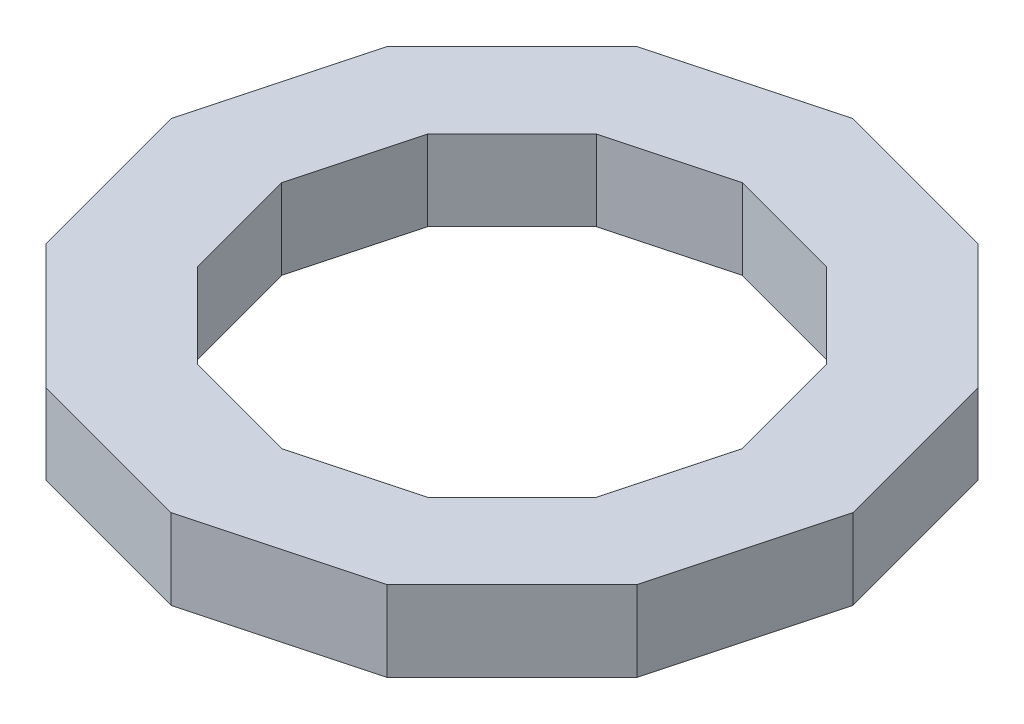
SolidWorks part; units mm, degrees
ref_plane "Front Plane" through (0, 0, 0) normal (0, 0, 1) x (1, 0, 0)
ref_plane "Top Plane" through (0, 0, 0) normal (0, 1, 0) x (1, 0, 0)
ref_plane "Right Plane" through (0, 0, 0) normal (1, 0, 0) x (0, 0, -1)
sketch "Sketch1" plane through (0, 0, 0) normal (0, 1, 0) x (1, 0, 0)
  line L0 (0, 0) -> (54.6679, 0) construction
  line L1 (54.6679, 0) -> (47.3438, 27.3339)
  line L2 (47.3438, 27.3339) -> (27.3339, 47.3438)
  line L3 (27.3339, 47.3438) -> (0, 54.6679)
  line L4 (0, 54.6679) -> (-27.3339, 47.3438)
  line L5 (-27.3339, 47.3438) -> (-47.3438, 27.3339)
  line L6 (-47.3438, 27.3339) -> (-54.6679, 0)
  line L7 (-54.6679, 0) -> (-47.3438, -27.3339)
  line L8 (-47.3438, -27.3339) -> (-27.3339, -47.3438)
  line L9 (-27.3339, -47.3438) -> (0, -54.6679)
  line L10 (0, -54.6679) -> (27.3339, -47.3438)
  line L11 (27.3339, -47.3438) -> (47.3438, -27.3339)
  line L12 (47.3438, -27.3339) -> (54.6679, 0)
  line L13 (80.9639, 0) -> (70.1168, 40.482)
  line L14 (70.1168, 40.482) -> (40.482, 70.1168)
  line L15 (40.482, 70.1168) -> (0, 80.9639)
  line L16 (0, 80.9639) -> (-40.482, 70.1168)
  line L17 (-40.482, 70.1168) -> (-70.1168, 40.482)
  line L18 (-70.1168, 40.482) -> (-80.9639, 0)
  line L19 (-80.9639, 0) -> (-70.1168, -40.482)
  line L20 (-70.1168, -40.482) -> (-40.482, -70.1168)
  line L21 (-40.482, -70.1168) -> (0, -80.9639)
  line L22 (0, -80.9639) -> (40.482, -70.1168)
  line L23 (40.482, -70.1168) -> (70.1168, -40.482)
  line L24 (70.1168, -40.482) -> (80.9639, 0)
  line L25 (70.1168, 40.482) -> (47.3438, 27.3339) construction
  circle A0 centre (0, 0) radius 52.8051 construction
  circle A1 centre (0, 0) radius 78.2051 construction
  dimension "D1" = 25.4
  dimension "D2" = 41.91
  dimension "D3" = 105
extrude "Boss-Extrude1" add sketch "Sketch1" along normal blind 19.05
